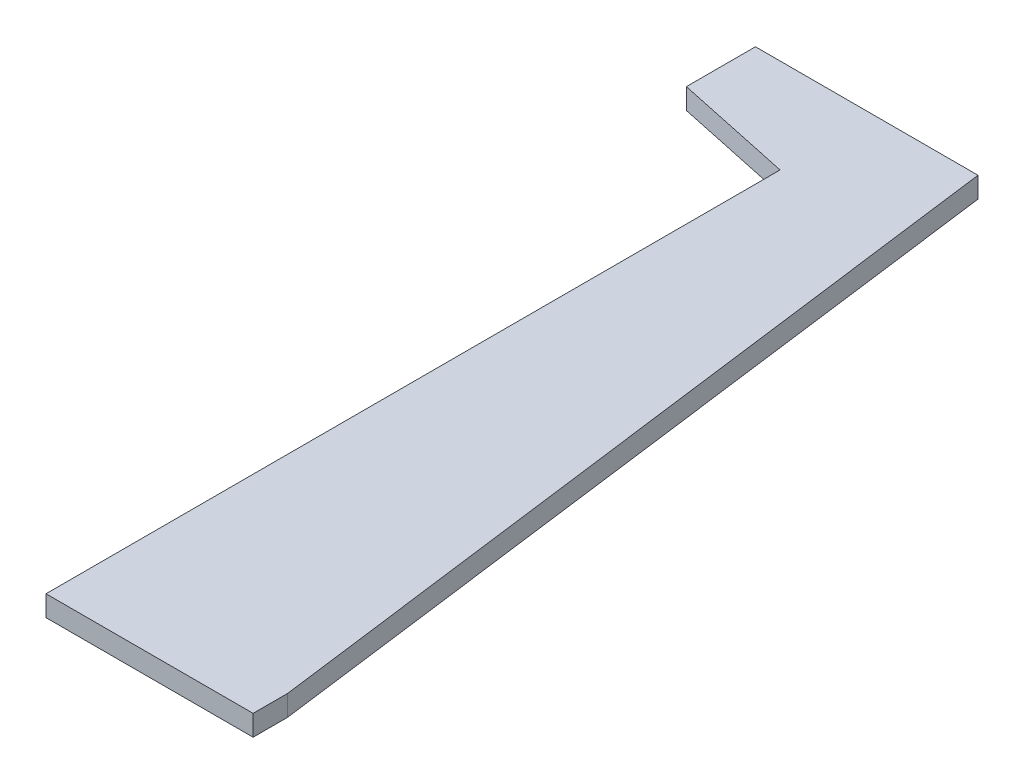
SolidWorks part; units mm, degrees
ref_plane "Спереди" through (0, 0, 0) normal (0, 0, 1) x (1, 0, 0)
ref_plane "Сверху" through (0, 0, 0) normal (0, 1, 0) x (1, 0, 0)
ref_plane "Справа" through (0, 0, 0) normal (1, 0, 0) x (0, 0, -1)
other "Configuration Table"
sketch "Эскиз1" plane through (0, 0, 0) normal (0, 1, 0) x (1, 0, 0)
  line L0 (0, 0) -> (0, 106.3304)
  line L1 (0, 120) -> (15, 120)
  line L2 (0, 0) -> (30, 0)
  line L3 (30, 0) -> (30, 5)
  line L6 (0, 120) -> (-17.2367, 120)
  line L7 (-17.2367, 120) -> (-17.2367, 110)
  line L8 (-17.2367, 110) -> (0, 106.3304)
  line L10 (15, 120) -> (30, 5)
  dimension "D1" = 120
  dimension "D2" = 15
  dimension "D3" = 30
  dimension "D4" = 5
  dimension "D6" = 10
extrude "Бобышка-Вытянуть1" add sketch "Эскиз1" along normal blind 3
